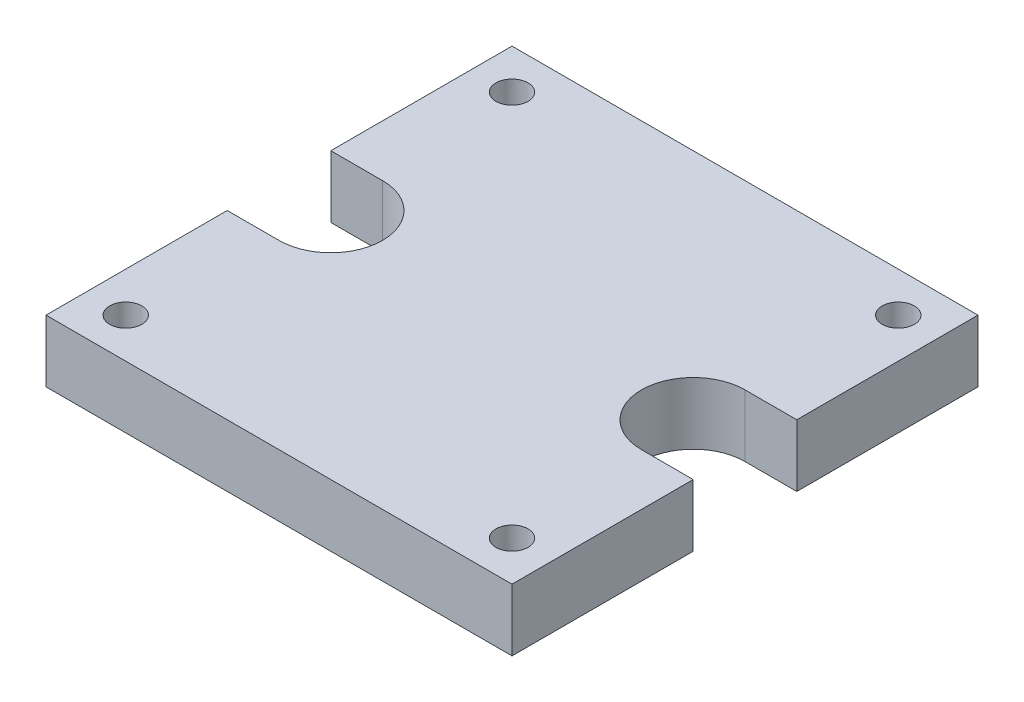
SolidWorks part; units mm, degrees
ref_plane "Front Plane" through (0, 0, 0) normal (0, 0, 1) x (1, 0, 0)
ref_plane "Top Plane" through (0, 0, 0) normal (0, 1, 0) x (1, 0, 0)
ref_plane "Right Plane" through (0, 0, 0) normal (1, 0, 0) x (0, 0, -1)
sketch "Sketch1" plane through (0, 0, 0) normal (0, 1, 0) x (1, 0, 0)
  line L0 (27.5, 0) -> (17.5, 0) construction
  line L1 (-18.65, -18.65) -> (18.65, -18.65) construction
  line L2 (-18.65, -18.65) -> (-18.65, 18.65) construction
  line L3 (-18.65, 18.65) -> (18.65, 18.65) construction
  line L4 (18.65, -18.65) -> (18.65, 18.65) construction
  line L5 (-18.65, -18.65) -> (18.65, 18.65) construction
  line L6 (-18.65, 18.65) -> (18.65, -18.65) construction
  line L7 (-22.5, -22.5) -> (22.5, -22.5)
  line L8 (-22.5, -22.5) -> (-22.5, 22.5)
  line L9 (-22.5, 22.5) -> (22.5, 22.5)
  line L10 (22.5, -22.5) -> (22.5, 22.5)
  line L11 (-22.5, -22.5) -> (22.5, 22.5) construction
  line L12 (-22.5, 22.5) -> (22.5, -22.5) construction
  line L13 (27.5, -5) -> (17.5, -5)
  line L14 (27.5, 5) -> (17.5, 5)
  line L15 (-27.5, 0) -> (-17.5, 0) construction
  line L16 (-27.5, 5) -> (-17.5, 5)
  line L17 (-27.5, -5) -> (-17.5, -5)
  circle A0 centre (18.65, -18.65) radius 1.55
  circle A1 centre (18.65, 18.65) radius 1.55
  circle A2 centre (-18.65, 18.65) radius 1.55
  circle A3 centre (-18.65, -18.65) radius 1.55
  arc A4 (27.5, -5) -> (27.5, 5) centre (27.5, 0) ccw
  arc A5 (17.5, 5) -> (17.5, -5) centre (17.5, 0) ccw
  arc A6 (-27.5, 5) -> (-27.5, -5) centre (-27.5, 0) ccw
  arc A7 (-17.5, -5) -> (-17.5, 5) centre (-17.5, 0) ccw
  point P0 (0, 0)
  point P10 (0, 0)
  point P17 (22.5, 0)
  point P23 (-22.5, 0)
  point P29 (16.5818, 0)
  dimension "D2" = 3.1
  dimension "D4" = 5
  dimension "D1" = 37.3
  dimension "D3" = 45
  dimension "D5" = 10
extrude "Boss-Extrude1" add sketch "Sketch1" along normal blind 6 contours A7 L17 L8 L7 L10 L13 A5 L14 L9 L16 A3 A2 A1 A0
